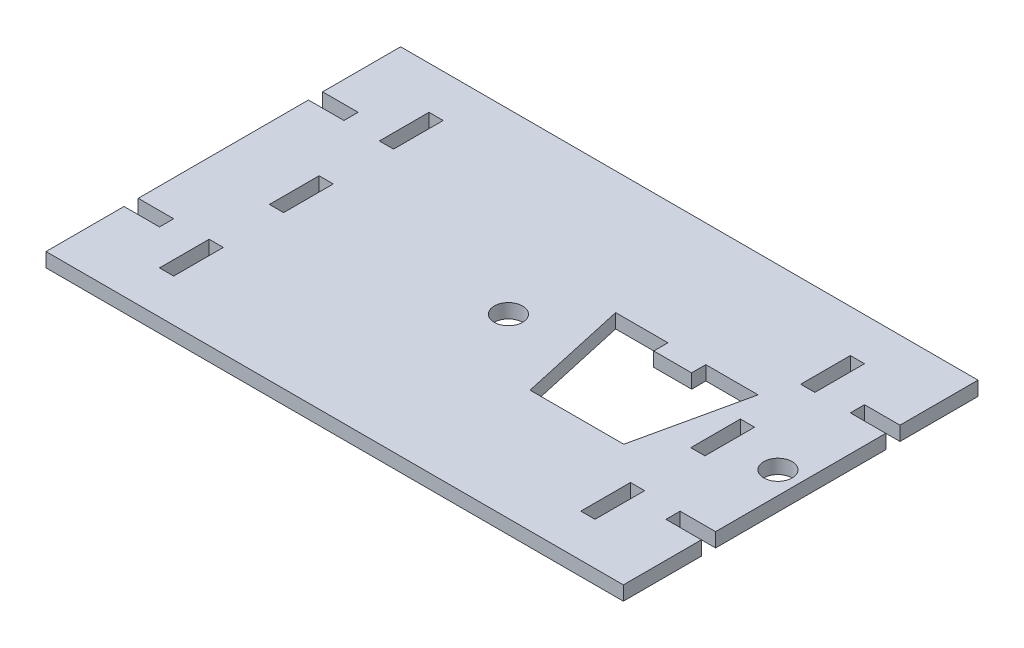
SolidWorks part; units mm, degrees
ref_plane "Front Plane" through (0, 0, 0) normal (0, 0, 1) x (1, 0, 0)
ref_plane "Top Plane" through (0, 0, 0) normal (0, 1, 0) x (1, 0, 0)
ref_plane "Right Plane" through (0, 0, 0) normal (1, 0, 0) x (0, 0, -1)
sketch "Sketch2" plane through (0, 0, 0) normal (0, 1, 0) x (1, 0, 0)
  line L1 (-50, 25) -> (50, 25)
  line L2 (-50, 25) -> (-50, -25)
  line L3 (-50, -25) -> (50, -25)
  line L4 (50, 25) -> (50, -25)
  line L5 (-50, 25) -> (50, -25) construction
  line L6 (-50, -25) -> (50, 25) construction
  point P0 (0, 0)
  point P12 (0, 0)
  point P13 (0, 0)
  dimension "D1" = 100
  dimension "D2" = 50
extrude "Boss-Extrude1" add sketch "Sketch2" along normal blind 2
sketch "Sketch12" plane through (0, 2, 0) normal (0, 1, 0) x (1, 0, 0)
  line L0 (-50, -25) -> (50, -25) construction
  line L1 (-40.2, -25) -> (-50, -25)
  line L2 (-40.2, -25) -> (-40.2, 25)
  line L3 (-40.2, 25) -> (-50, 25)
  line L4 (-50, -25) -> (-50, 25)
  line L5 (-50, -25) -> (50, -25) construction
  line L6 (41.2, -25) -> (50, -25)
  line L7 (41.2, -25) -> (41.2, 25)
  line L8 (41.2, 25) -> (50, 25)
  line L9 (50, -25) -> (50, 25)
extrude "Cut-Extrude8" cut sketch "Sketch12" against normal blind 6
sketch "Sketch13" plane through (0, 2, 0) normal (0, 1, 0) x (1, 0, 0)
  line L0 (-40.2, -25) -> (-40.2, 25) construction
  line L1 (-28.2, 19) -> (-30.2, 19)
  line L2 (-28.2, 19) -> (-28.2, 12)
  line L3 (-28.2, 12) -> (-30.2, 12)
  line L4 (-30.2, 19) -> (-30.2, 12)
  line L5 (-28.2, 3.5) -> (-30.2, 3.5)
  line L6 (-28.2, 3.5) -> (-28.2, -3.5)
  line L7 (-28.2, -3.5) -> (-30.2, -3.5)
  line L8 (-30.2, 3.5) -> (-30.2, -3.5)
  line L9 (-28.2, -12) -> (-30.2, -12)
  line L10 (-28.2, -12) -> (-28.2, -19)
  line L11 (-28.2, -19) -> (-30.2, -19)
  line L12 (-30.2, -12) -> (-30.2, -19)
  line L13 (29.2, 19) -> (31.2, 19)
  line L14 (29.2, 19) -> (29.2, 12)
  line L15 (29.2, 12) -> (31.2, 12)
  line L16 (31.2, 19) -> (31.2, 12)
  line L17 (29.2, 3.5) -> (31.2, 3.5)
  line L18 (29.2, 3.5) -> (29.2, -3.5)
  line L19 (29.2, -3.5) -> (31.2, -3.5)
  line L20 (31.2, 3.5) -> (31.2, -3.5)
  line L21 (29.2, -12) -> (31.2, -12)
  line L22 (29.2, -12) -> (29.2, -19)
  line L23 (29.2, -19) -> (31.2, -19)
  line L24 (31.2, -12) -> (31.2, -19)
  line L25 (41.2, 25) -> (-40.2, 25) construction
  line L26 (41.2, 25) -> (41.2, -25) construction
  line L27 (41.2, 25) -> (-40.2, 25) construction
  line L28 (-40.2, -25) -> (41.2, -25) construction
  line L29 (41.2, 25) -> (-40.2, 25) construction
  line L30 (-40.2, -25) -> (41.2, -25) construction
  line L31 (-40.2, 14) -> (-35.2, 14)
  line L32 (-40.2, 14) -> (-40.2, 12)
  line L33 (-40.2, 12) -> (-35.2, 12)
  line L34 (-35.2, 14) -> (-35.2, 12)
  line L35 (-40.2, -12) -> (-35.2, -12)
  line L36 (-40.2, -12) -> (-40.2, -14)
  line L37 (-40.2, -14) -> (-35.2, -14)
  line L38 (-35.2, -12) -> (-35.2, -14)
  line L40 (41.2, 14) -> (36.2, 14)
  line L41 (41.2, 14) -> (41.2, 12)
  line L42 (41.2, 12) -> (36.2, 12)
  line L43 (36.2, 14) -> (36.2, 12)
  line L44 (41.2, -12) -> (36.2, -12)
  line L45 (41.2, -12) -> (41.2, -14)
  line L46 (41.2, -14) -> (36.2, -14)
  line L47 (36.2, -12) -> (36.2, -14)
  point P30 (30.2, 3.5)
  dimension "D1" = 2
  dimension "D2" = 2
  dimension "D3" = 2
  dimension "D4" = 2
  dimension "D5" = 2
  dimension "D6" = 2
  dimension "D7" = 10
  dimension "D8" = 10
  dimension "D9" = 10
  dimension "D10" = 7
  dimension "D11" = 7
  dimension "D12" = 7
  dimension "D13" = 7
  dimension "D14" = 7
  dimension "D15" = 7
  dimension "D16" = 10
  dimension "D17" = 10
  dimension "D18" = 10
  dimension "D19" = 6
  dimension "D20" = 8.5
  dimension "D21" = 8.5
  dimension "D22" = 6
  dimension "D23" = 6
  dimension "D24" = 8.5
  dimension "D25" = 8.5
  dimension "D26" = 6
  dimension "D27" = 2
  dimension "D28" = 2
  dimension "D29" = 11
  dimension "D30" = 5
  dimension "D31" = 5
  dimension "D32" = 11
  dimension "D33" = 24
  dimension "D34" = 2
  dimension "D35" = 2
  dimension "D36" = 5
  dimension "D37" = 5
  dimension "D38" = 0
  dimension "D39" = 0
  dimension "D40" = 11
  dimension "D41" = 11
  dimension "D42" = 24
extrude "Cut-Extrude10" cut sketch "Sketch13" against normal blind 6
sketch "Sketch14" plane through (0, 0, 0) normal (0, -1, 0) x (1, 0, 0)
  line L0 (41.2, -25) -> (-40.2, -25) construction
  line L2 (20.1257, -5.7) -> (20.1257, -7.7)
  line L4 (14.7839, -5.7) -> (20.1257, -5.7)
  line L5 (20.1257, -5.7) -> (25.0043, -5.7)
  line L6 (25.0043, -5.7) -> (22.4548, 5.8)
  line L7 (22.4548, 5.8) -> (12.4548, 5.8)
  line L8 (12.4548, 5.8) -> (9.9053, -5.7)
  line L9 (9.9053, -5.7) -> (14.7839, -5.7)
  line L10 (14.7839, -5.7) -> (14.7839, -7.7)
  line L11 (14.7839, -7.7) -> (7.4134, -7.7)
  line L12 (7.4134, -7.7) -> (10.8497, 7.8)
  line L13 (10.8497, 7.8) -> (24.06, 7.8)
  line L14 (24.06, 7.8) -> (27.4963, -7.7)
  line L15 (27.4963, -7.7) -> (20.1257, -7.7)
  circle A0 centre (0.0463, 0.05) radius 2
  circle A1 centre (38.0463, 0.05) radius 2
  point P4 (21.7868, -1.3748)
  point P5 (20.5907, -8.0745)
  point P6 (23.1645, -16.1491)
  point P21 (0, 0)
  point P22 (3.7151, 1.0821)
  point P23 (41.7151, -1)
  point P27 (-0.5678, -1)
  point P29 (3.7151, -1)
  line M84 (41.2, -12) -> (41.2, 12)
  dimension "D1" = 4
  dimension "D2" = 4
  dimension "D28" = 7.75
  dimension "D3" = 38
  dimension "D4" = 0
  dimension "D5" = 13.2103
  dimension "D6" = 15.8763
  dimension "D7" = 15.8763
  dimension "D8" = 7.3706
  dimension "D9" = 7.3706
  dimension "D10" = 11.7792
  dimension "D11" = 10
  dimension "D12" = 11.7792
  dimension "D13" = 180
  dimension "D14" = 77.5
  dimension "D15" = 77.5
  dimension "D16" = 102.5
  dimension "D17" = 102.5
  dimension "D18" = 2
  dimension "D19" = 2
  dimension "D20" = 2
  dimension "D21" = 2
  dimension "D22" = 2
  dimension "D23" = 4.8786
  dimension "D24" = 4.8786
  dimension "D25" = 0
  dimension "D26" = 5.14
  dimension "D27" = 17.3
  dimension "D29" = 10.55
extrude "Cut-Extrude11" cut sketch "Sketch14" against normal blind 2 contours L15 L14 L13 L12 L11 L10 L9 L8 L7 L6 L5 L2 | L8 L9 L4 L5 L6 L7 | A0 | A1 M84
